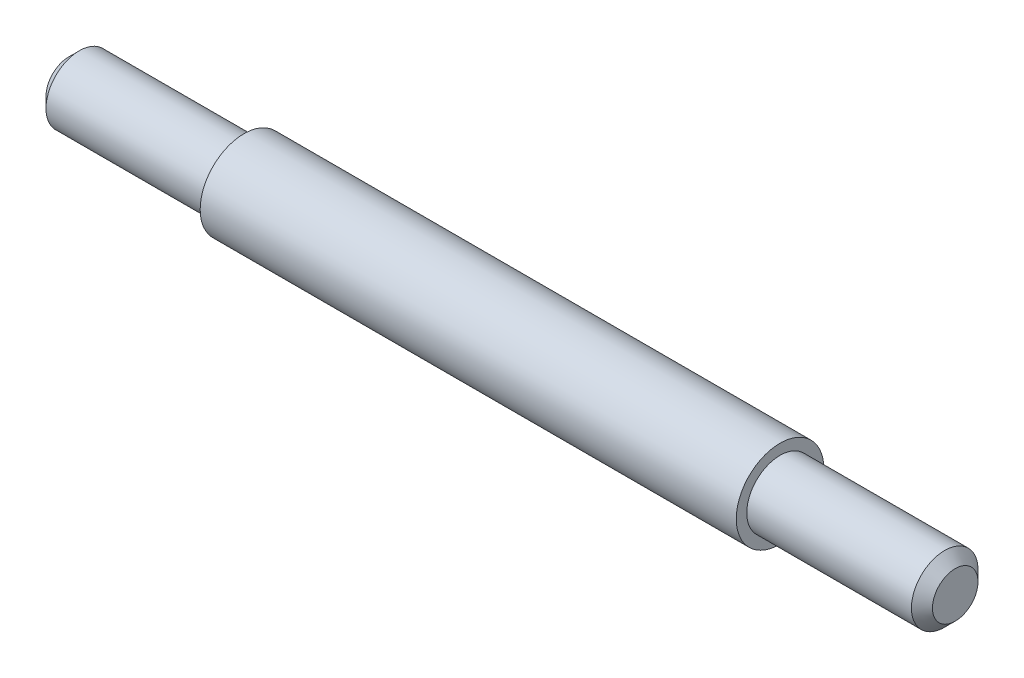
SolidWorks part; units mm, degrees
ref_plane "Front Plane" through (0, 0, 0) normal (0, 0, 1) x (1, 0, 0)
ref_plane "Top Plane" through (0, 0, 0) normal (0, 1, 0) x (1, 0, 0)
ref_plane "Right Plane" through (0, 0, 0) normal (1, 0, 0) x (0, 0, -1)
sketch "Sketch3" plane through (0, 0, 0) normal (0, 0, 1) x (1, 0, 0)
  line L0 (-32.131, 0) -> (32.131, 0)
  line L1 (-32.131, 0) -> (-32.131, 2.413)
  line L2 (-32.131, 2.413) -> (-19.431, 2.413)
  line L3 (-19.431, 2.413) -> (-19.431, 3.175)
  line L4 (-19.431, 3.175) -> (19.431, 3.175)
  line L5 (19.431, 3.175) -> (19.431, 2.413)
  line L6 (19.431, 2.413) -> (32.131, 2.413)
  line L7 (32.131, 2.413) -> (32.131, 0)
  dimension "D1" = 2.413
  dimension "D2" = 3.175
  dimension "D3" = 12.7
  dimension "D4" = 12.7
  dimension "D5" = 38.862
  dimension "D6" = 19.431
  dimension "D7" = 2.413
revolve "Revolve1" add sketch "Sketch3" angle 360 about L0
chamfer "Chamfer1" distance 0.762 1 edges at (-32.131, 0, 2.413)
chamfer "Chamfer2" distance 0.762 1 edges at (32.131, 0, 2.413)
